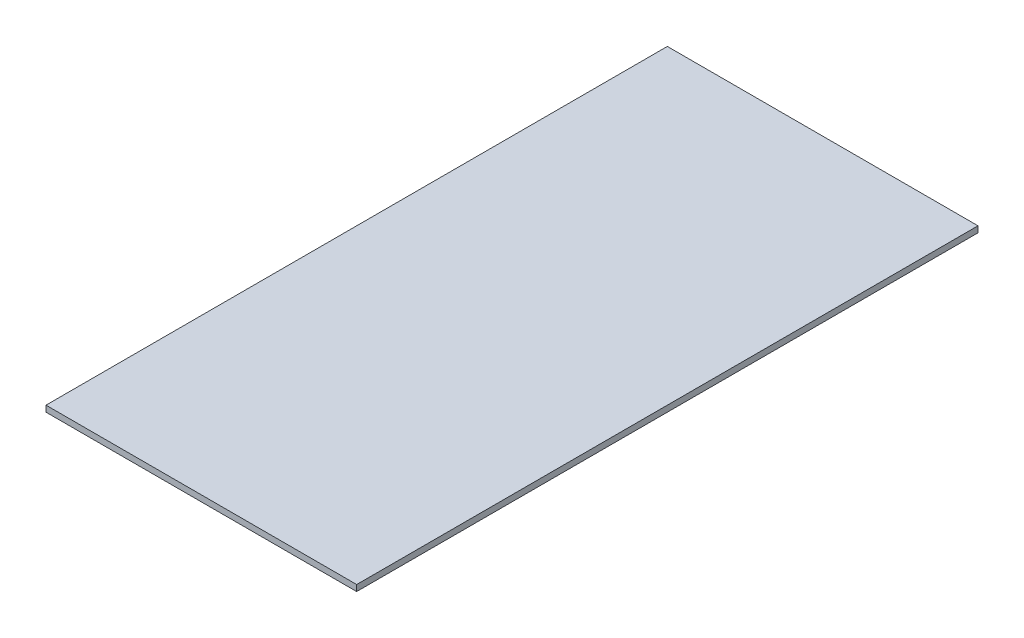
SolidWorks part; units mm, degrees
ref_plane "Front Plane" through (0, 0, 0) normal (0, 0, 1) x (1, 0, 0)
ref_plane "Top Plane" through (0, 0, 0) normal (0, 1, 0) x (1, 0, 0)
ref_plane "Right Plane" through (0, 0, 0) normal (1, 0, 0) x (0, 0, -1)
sketch "Sketch1" plane through (0, 0, 0) normal (0, 1, 0) x (1, 0, 0)
  line L1 (-25.4, -50.8) -> (25.4, -50.8)
  line L2 (-25.4, -50.8) -> (-25.4, 50.8)
  line L3 (-25.4, 50.8) -> (25.4, 50.8)
  line L4 (25.4, -50.8) -> (25.4, 50.8)
  line L5 (-25.4, -50.8) -> (25.4, 50.8) construction
  line L6 (-25.4, 50.8) -> (25.4, -50.8) construction
  point P0 (0, 0)
  dimension "D1" = 50.8
  dimension "D2" = 101.6
extrude "Boss-Extrude1" add sketch "Sketch1" along normal blind 1
